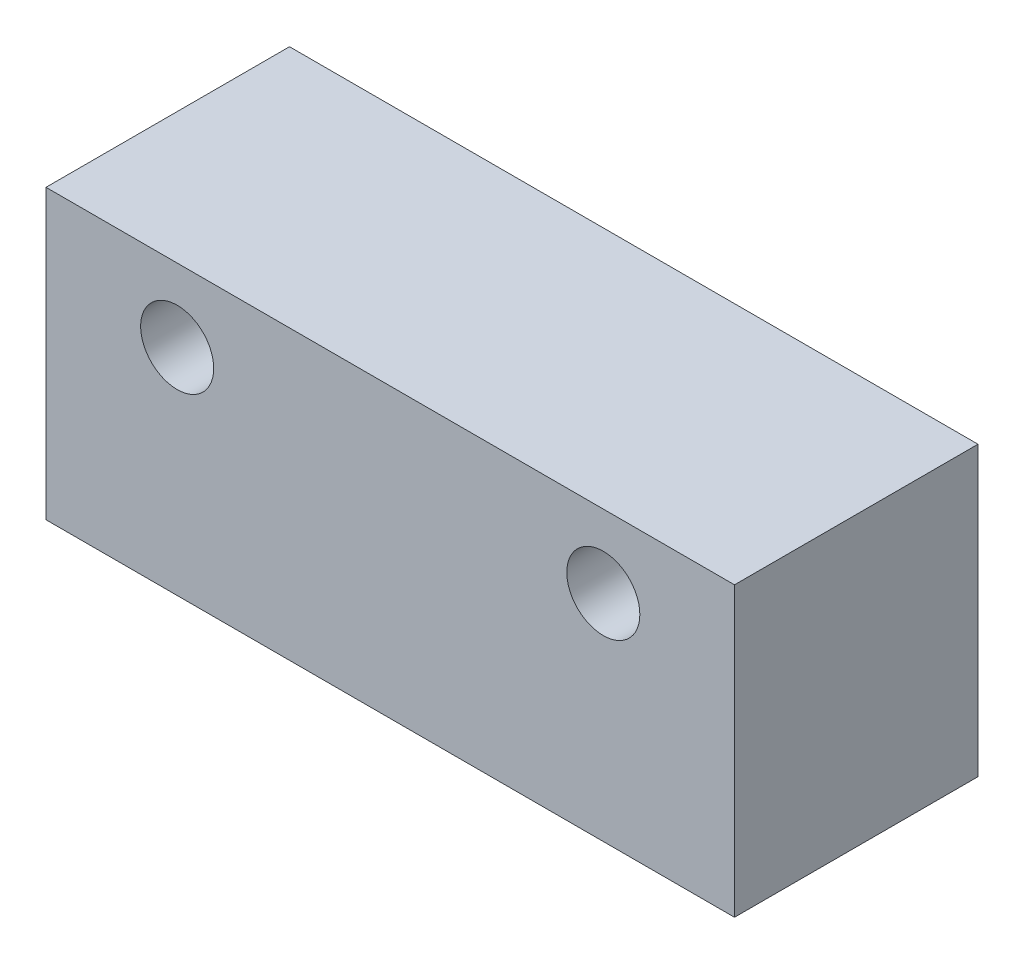
SolidWorks part; units mm, degrees
material "6061-T6 (SS)"
ref_plane "X-Y Datum" through (0, 0, 0) normal (0, 0, 1) x (1, 0, 0)
ref_plane "X-Z Datum" through (0, 0, 0) normal (0, 1, 0) x (1, 0, 0)
ref_plane "Y-Z Datum" through (0, 0, 0) normal (1, 0, 0) x (0, 0, -1)
sketch "Sketch1" plane through (0, 0, 0) normal (0, 0, 1) x (1, 0, 0)
  line L1 (-28.275, 11.825) -> (28.275, 11.825)
  line L2 (-28.275, 11.825) -> (-28.275, -11.825)
  line L3 (-28.275, -11.825) -> (28.275, -11.825)
  line L4 (28.275, 11.825) -> (28.275, -11.825)
  line L5 (-28.275, 11.825) -> (28.275, -11.825) construction
  line L6 (-28.275, -11.825) -> (28.275, 11.825) construction
  point P0 (0, 0)
  dimension "D1" = 56.55
  dimension "D2" = 23.65
extrude "Boss-Extrude1" add sketch "Sketch1" along normal blind 20 contours L2 L3 L4 L1
sketch "Sketch2" plane through (0, 0, 20) normal (0, 0, 1) x (1, 0, 0)
  line L0 (-23.5453, 5.825) -> (31.0951, 5.825) construction
  line L1 (0, 11.825) -> (0, -11.825) construction
  line L2 (-28.275, 11.825) -> (28.275, 11.825) construction
  line L3 (-17.5, 5.825) -> (17.5, 5.825) construction
  line L4 (-28.275, -11.825) -> (28.275, -11.825) construction
  circle A0 centre (17.5, 5.825) radius 3
  circle A1 centre (-17.5, 5.825) radius 3
  point P10 (0, 5.825)
  dimension "D1" = 6
  dimension "D2" = 35
  dimension "D3" = 6
extrude "Cut-Extrude1" cut sketch "Sketch2" against normal blind 12 contours A1 L0 L3 | L0 A1 L3 | L0 L3 A0 | L3 L0 A0
